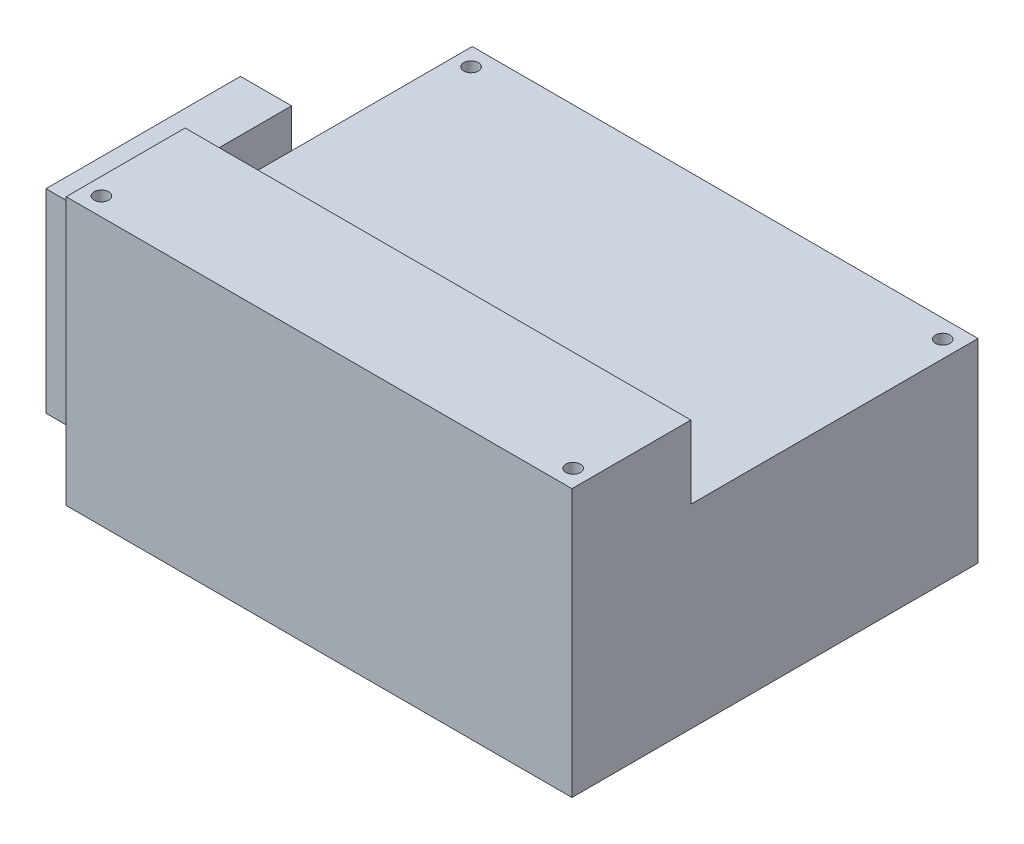
SolidWorks part; units mm, degrees
ref_plane "Front Plane" through (0, 0, 0) normal (0, 0, 1) x (1, 0, 0)
ref_plane "Top Plane" through (0, 0, 0) normal (0, 1, 0) x (1, 0, 0)
ref_plane "Right Plane" through (0, 0, 0) normal (1, 0, 0) x (0, 0, -1)
sketch "Sketch1" plane through (0, 0, 0) normal (0, 1, 0) x (1, 0, 0)
  line L1 (0, 0) -> (104, 0)
  line L2 (0, 0) -> (0, 83.5)
  line L3 (0, 83.5) -> (104, 83.5)
  line L4 (104, 0) -> (104, 83.5)
  dimension "D1" = 104
  dimension "D2" = 83.5
extrude "Boss-Extrude1" add sketch "Sketch1" along normal blind 55
sketch "Sketch2" plane through (104, 0, 0) normal (1, 0, 0) x (0, 0, -1)
  line L0 (0, 0) -> (83.5, 0) construction
  line L1 (83.5, 55) -> (24.4578, 55)
  line L2 (83.5, 55) -> (83.5, 40)
  line L3 (83.5, 40) -> (24.4578, 40)
  line L4 (24.4578, 55) -> (24.4578, 40)
  dimension "D1" = 40
extrude "Cut-Extrude1" cut sketch "Sketch2" against normal through all
sketch "Sketch3" plane through (0, 0, 0) normal (0, -1, 0) x (1, 0, 0)
  line L0 (0, -83.5) -> (104, 0) construction
  line L2 (100.5, -3.75) -> (3.5, -3.75) construction
  line L3 (100.5, -3.75) -> (100.5, -79.75) construction
  line L4 (0, 0) -> (0, -83.5)
  line L5 (0, -83.5) -> (104, -83.5)
  line L6 (104, -83.5) -> (104, 0)
  line L7 (104, 0) -> (0, 0)
  line L8 (0, 0) -> (0, -83.5) construction
  line L9 (0, -83.5) -> (104, -83.5) construction
  line L10 (104, -83.5) -> (104, 0) construction
  line L11 (104, 0) -> (0, 0) construction
  line L12 (100.5, -79.75) -> (3.5, -79.75) construction
  line L13 (3.5, -3.75) -> (3.5, -79.75) construction
  line L14 (100.5, -3.75) -> (3.5, -79.75) construction
  line L15 (100.5, -79.75) -> (3.5, -3.75) construction
  circle A0 centre (3.5, -79.75) radius 1.5
  circle A1 centre (3.5, -3.75) radius 1.5
  circle A2 centre (100.5, -3.75) radius 1.5
  circle A3 centre (100.5, -79.75) radius 1.5
  point P2 (52, -41.75)
  dimension "D3" = 3
  dimension "D2" = 97
  dimension "D4" = 76
  dimension "D1" = 0
extrude "Cut-Extrude2" cut sketch "Sketch3" against normal through all
sketch "Sketch4" plane through (0, 0, 0) normal (-1, 0, 0) x (0, 0, 1)
  line L0 (0, 55) -> (0, 0) construction
  line L1 (-46.35, 8) -> (-6.35, 8)
  line L2 (-46.35, 8) -> (-46.35, 48)
  line L3 (-46.35, 48) -> (-6.35, 48)
  line L4 (-6.35, 8) -> (-6.35, 48)
  line L5 (-83.5, 0) -> (0, 0) construction
  dimension "D1" = 40
  dimension "D2" = 40
  dimension "D3" = 6.35
  dimension "D4" = 8
extrude "Boss-Extrude2" add sketch "Sketch4" along normal blind 10.5
